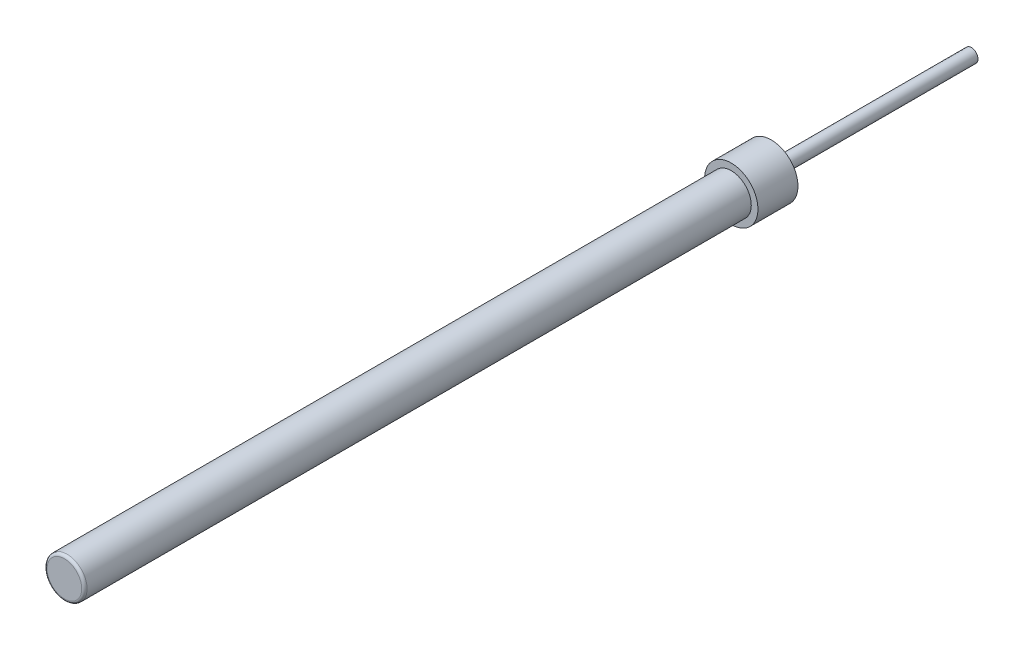
SolidWorks part; units mm, degrees
material "201 Annealed Stainless Steel (SS)"
ref_plane "Front Plane" through (0, 0, 0) normal (0, 0, 1) x (1, 0, 0)
ref_plane "Top Plane" through (0, 0, 0) normal (0, 1, 0) x (1, 0, 0)
ref_plane "Right Plane" through (0, 0, 0) normal (1, 0, 0) x (0, 0, -1)
sketch "Sketch1" plane through (0, 0, 0) normal (0, 0, 1) x (1, 0, 0)
  circle A0 centre (0, 0) radius 1.5
  dimension "D1" = 3
extrude "Boss-Extrude1" add sketch "Sketch1" along normal blind 50
fillet "Fillet2" radius 0.2 1 edges at (1.5, 0, 50)
sketch "Sketch2" plane through (0, 0, 0) normal (0, 0, -1) x (-1, 0, 0)
  circle A0 centre (0, 0) radius 2
  dimension "D1" = 4
extrude "Boss-Extrude2" add sketch "Sketch2" along normal blind 3
sketch "Sketch3" plane through (0, 0, -3) normal (0, 0, -1) x (-1, 0, 0)
  circle A0 centre (0, 0) radius 0.5
  dimension "D1" = 1
extrude "Boss-Extrude3" add sketch "Sketch3" along normal blind 15
